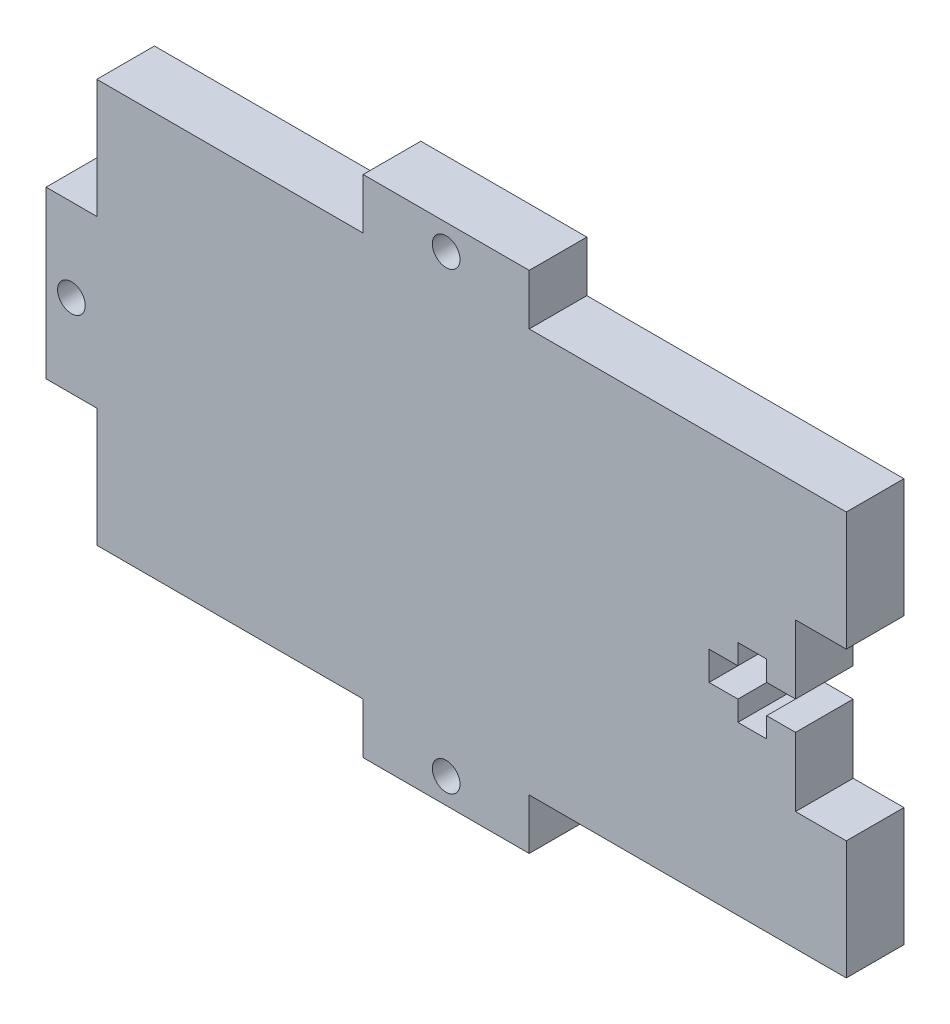
SolidWorks part; units mm, degrees
ref_plane "Front Plane" through (0, 0, 0) normal (0, 0, 1) x (1, 0, 0)
ref_plane "Top Plane" through (0, 0, 0) normal (0, 1, 0) x (1, 0, 0)
ref_plane "Right Plane" through (0, 0, 0) normal (1, 0, 0) x (0, 0, -1)
sketch "Sketch1" plane through (0, 0, 0) normal (0, 0, 1) x (1, 0, 0)
  line L1 (0, 0) -> (82.55, 0)
  line L2 (0, 0) -> (0, 44.45)
  line L3 (0, 44.45) -> (82.55, 44.45)
  line L4 (82.55, 0) -> (82.55, 44.45)
  dimension "D1" = 44.45
  dimension "D2" = 82.55
extrude "Boss-Extrude1" add sketch "Sketch1" along normal blind 6.35
sketch "Sketch2" plane through (0, 0, 6.35) normal (0, 0, 1) x (1, 0, 0)
  line L0 (0, -1.7462) -> (0, 1.7462) construction
  line L1 (0, 31.369) -> (-5.588, 31.369)
  line L2 (0, 31.369) -> (0, 13.081)
  line L3 (0, 13.081) -> (-5.588, 13.081)
  line L4 (-5.588, 31.369) -> (-5.588, 13.081)
  line L6 (0, 44.45) -> (0, 0) construction
  point P6 (-5.588, 22.225)
  point P7 (0, 22.225)
  dimension "D1" = 5.588
  dimension "D2" = 18.288
extrude "Boss-Extrude2" add sketch "Sketch2" against normal blind 6.35
sketch "Sketch5" plane through (0, 0, 6.35) normal (0, 0, 1) x (1, 0, 0)
  line L0 (82.55, 44.45) -> (0, 44.45) construction
  line L1 (29.337, 44.45) -> (47.625, 44.45)
  line L2 (29.337, 44.45) -> (29.337, 50.038)
  line L3 (29.337, 50.038) -> (47.625, 50.038)
  line L4 (47.625, 44.45) -> (47.625, 50.038)
  line L6 (-5.588, 22.225) -> (82.55, 22.225) construction
  line L7 (47.625, 0) -> (47.625, -5.588)
  line L8 (29.337, -5.588) -> (47.625, -5.588)
  line L9 (29.337, 0) -> (29.337, -5.588)
  line L10 (29.337, 0) -> (47.625, 0)
  line L13 (-5.588, 31.369) -> (-5.588, 13.081) construction
  line L14 (82.55, 0) -> (82.55, 44.45) construction
  point P12 (38.481, 0)
  point P18 (38.481, 22.225)
  point P19 (38.481, 44.45)
  dimension "D1" = 18.288
  dimension "D2" = 5.588
extrude "Boss-Extrude3" add sketch "Sketch5" against normal blind 6.35
sketch "Sketch3" plane through (0, 0, 6.35) normal (0, 0, 1) x (1, 0, 0)
  line L0 (82.55, 0) -> (82.55, 44.45) construction
  line L1 (82.55, 13.081) -> (76.962, 13.081)
  line L2 (82.55, 13.081) -> (82.55, 31.369)
  line L3 (82.55, 31.369) -> (76.962, 31.369)
  line L4 (76.962, 13.081) -> (76.962, 31.369)
  line L22 (0, 44.45) -> (0, 31.369)
  line L23 (0, 31.369) -> (-5.588, 31.369)
  line L24 (-5.588, 31.369) -> (-5.588, 13.081)
  line L25 (-5.588, 13.081) -> (0, 13.081)
  line L26 (0, 13.081) -> (0, 0)
  line L27 (0, 0) -> (29.337, 0)
  line L28 (29.337, 0) -> (29.337, -5.588)
  line L29 (29.337, -5.588) -> (47.625, -5.588)
  line L30 (47.625, -5.588) -> (47.625, 0)
  line L31 (47.625, 0) -> (82.55, 0)
  line L32 (82.55, 0) -> (82.55, 44.45)
  line L33 (82.55, 44.45) -> (47.625, 44.45)
  line L34 (47.625, 44.45) -> (47.625, 50.038)
  line L35 (47.625, 50.038) -> (29.337, 50.038)
  line L36 (29.337, 50.038) -> (29.337, 44.45)
  line L37 (29.337, 44.45) -> (0, 44.45)
  line L40 (-5.588, 31.369) -> (-5.588, 13.081) construction
  point P6 (76.962, 22.225)
  point P11 (-5.588, 22.225)
  dimension "D1" = 18.288
  dimension "D2" = 5.588
  dimension "D4" = 0
extrude "Cut-Extrude1" cut sketch "Sketch3" against normal through all
sketch "Sketch6" plane through (0, 0, 6.35) normal (0, 0, 1) x (1, 0, 0)
  line L0 (76.962, 31.369) -> (76.962, 13.081) construction
  line L1 (67.437, 23.8125) -> (70.612, 23.8125)
  line L2 (67.437, 23.8125) -> (67.437, 20.6375)
  line L3 (67.437, 20.6375) -> (70.612, 20.6375)
  line L4 (76.962, 23.8125) -> (76.962, 20.6375)
  line L5 (67.437, 23.8125) -> (76.962, 20.6375) construction
  line L6 (67.437, 20.6375) -> (76.962, 23.8125) construction
  line L7 (70.612, 18.415) -> (73.787, 18.415)
  line L8 (70.612, 18.415) -> (70.612, 20.6375)
  line L9 (70.612, 26.035) -> (73.787, 26.035)
  line L10 (73.787, 18.415) -> (73.787, 20.6375)
  line L11 (70.612, 18.415) -> (73.787, 26.035) construction
  line L12 (70.612, 26.035) -> (73.787, 18.415) construction
  line L13 (70.612, 23.8125) -> (70.612, 26.035)
  line L14 (73.787, 23.8125) -> (76.962, 23.8125)
  line L15 (73.787, 23.8125) -> (73.787, 26.035)
  line L16 (73.787, 20.6375) -> (76.962, 20.6375)
  line L17 (-2.794, 31.369) -> (-2.794, 13.081) construction
  line L18 (0, 31.369) -> (-5.588, 31.369) construction
  line L19 (-5.588, 13.081) -> (0, 13.081) construction
  line L20 (29.337, 50.038) -> (29.337, 44.45) construction
  line L21 (47.625, 44.45) -> (47.625, 50.038) construction
  line L22 (47.625, -5.588) -> (47.625, 0) construction
  line L23 (29.337, 0) -> (29.337, -5.588) construction
  line L24 (29.337, 50.038) -> (29.337, 44.45) construction
  line L25 (47.625, 44.45) -> (47.625, 50.038) construction
  line L26 (47.625, -5.588) -> (47.625, 0) construction
  line L27 (29.337, 0) -> (29.337, -5.588) construction
  line L28 (29.337, 47.244) -> (47.625, 47.244) construction
  line L29 (29.337, -2.794) -> (47.625, -2.794) construction
  circle A0 centre (-2.794, 22.225) radius 1.524
  circle A1 centre (38.481, -2.794) radius 1.524
  circle A2 centre (38.481, 47.244) radius 1.524
  point P0 (72.1995, 22.225)
  point P5 (72.1995, 22.225)
  point P12 (76.962, 22.225)
  dimension "D4" = 3.048
  dimension "D5" = 3.048
  dimension "D6" = 3.048
  dimension "D1" = 3.175
  dimension "D2" = 7.62
  dimension "1/8" = 3.175
  dimension "D3" = 9.525
extrude "Cut-Extrude2" cut sketch "Sketch6" against normal through all
sketch "Sketch7" [suppressed] plane through (0, 0, 0) normal (0, 0, 1) x (1, 0, 0)
  line L0 (15.758, 28.5698) -> (17.4249, 28.5698)
  line L1 (15.758, 29.0778) -> (17.4249, 29.0778)
  line L2 (15.758, 29.0778) -> (15.758, 28.8238)
  line L3 (15.758, 28.8238) -> (17.4249, 28.8238)
  line L4 (17.4249, 29.0778) -> (17.4249, 28.8238)
  line L5 (15.758, 28.5698) -> (15.758, 28.3158)
  line L6 (15.758, 28.3158) -> (17.4249, 28.3158)
  line L7 (17.4249, 28.5698) -> (17.4249, 28.3158)
  line L8 (15.758, 28.0618) -> (17.4249, 28.0618)
  line L9 (15.758, 28.0618) -> (15.758, 27.8078)
  line L10 (15.758, 27.8078) -> (17.4249, 27.8078)
  line L11 (17.4249, 28.0618) -> (17.4249, 27.8078)
  line L12 (15.758, 27.5538) -> (17.4249, 27.5538)
  line L13 (15.758, 27.5538) -> (15.758, 27.2998)
  line L14 (15.758, 27.2998) -> (17.4249, 27.2998)
  line L15 (17.4249, 27.5538) -> (17.4249, 27.2998)
  line L16 (15.758, 27.0458) -> (17.4249, 27.0458)
  line L17 (15.758, 27.0458) -> (15.758, 26.7918)
  line L18 (15.758, 26.7918) -> (17.4249, 26.7918)
  line L19 (17.4249, 27.0458) -> (17.4249, 26.7918)
  line L20 (15.758, 26.5378) -> (17.4249, 26.5378)
  line L21 (15.758, 26.5378) -> (15.758, 26.2838)
  line L22 (15.758, 26.2838) -> (17.4249, 26.2838)
  line L23 (17.4249, 26.5378) -> (17.4249, 26.2838)
  line L24 (15.758, 26.0298) -> (17.4249, 26.0298)
  line L25 (15.758, 26.0298) -> (15.758, 25.7758)
  line L26 (15.758, 25.7758) -> (17.4249, 25.7758)
  line L27 (17.4249, 26.0298) -> (17.4249, 25.7758)
  line L28 (15.758, 25.5218) -> (17.4249, 25.5218)
  line L29 (15.758, 25.5218) -> (15.758, 25.2678)
  line L30 (15.758, 25.2678) -> (17.4249, 25.2678)
  line L31 (17.4249, 25.5218) -> (17.4249, 25.2678)
  line L32 (15.758, 25.0138) -> (17.4249, 25.0138)
  line L33 (15.758, 25.0138) -> (15.758, 24.7598)
  line L34 (15.758, 24.7598) -> (17.4249, 24.7598)
  line L35 (17.4249, 25.0138) -> (17.4249, 24.7598)
  line L36 (15.758, 24.5058) -> (17.4249, 24.5058)
  line L37 (15.758, 24.5058) -> (15.758, 24.2518)
  line L38 (15.758, 24.2518) -> (17.4249, 24.2518)
  line L39 (17.4249, 24.5058) -> (17.4249, 24.2518)
  line L40 (15.758, 23.9978) -> (17.4249, 23.9978)
  line L41 (15.758, 23.9978) -> (15.758, 23.7438)
  line L42 (15.758, 23.7438) -> (17.4249, 23.7438)
  line L43 (17.4249, 23.9978) -> (17.4249, 23.7438)
  line L44 (15.758, 23.4898) -> (17.4249, 23.4898)
  line L45 (15.758, 23.4898) -> (15.758, 23.2358)
  line L46 (15.758, 23.2358) -> (17.4249, 23.2358)
  line L47 (17.4249, 23.4898) -> (17.4249, 23.2358)
  line L48 (15.758, 22.9818) -> (17.4249, 22.9818)
  line L49 (15.758, 22.9818) -> (15.758, 22.7278)
  line L50 (15.758, 22.7278) -> (17.4249, 22.7278)
  line L51 (17.4249, 22.9818) -> (17.4249, 22.7278)
  line L52 (15.758, 22.4738) -> (17.4249, 22.4738)
  line L53 (15.758, 22.4738) -> (15.758, 22.2198)
  line L54 (15.758, 22.2198) -> (17.4249, 22.2198)
  line L55 (17.4249, 22.4738) -> (17.4249, 22.2198)
  line L56 (15.758, 21.9658) -> (17.4249, 21.9658)
  line L57 (15.758, 21.9658) -> (15.758, 21.7118)
  line L58 (15.758, 21.7118) -> (17.4249, 21.7118)
  line L59 (17.4249, 21.9658) -> (17.4249, 21.7118)
  line L60 (15.758, 21.4578) -> (17.4249, 21.4578)
  line L61 (15.758, 21.4578) -> (15.758, 21.2038)
  line L62 (15.758, 21.2038) -> (17.4249, 21.2038)
  line L63 (17.4249, 21.4578) -> (17.4249, 21.2038)
  line L64 (15.758, 20.9498) -> (17.4249, 20.9498)
  line L65 (15.758, 20.9498) -> (15.758, 20.6958)
  line L66 (15.758, 20.6958) -> (17.4249, 20.6958)
  line L67 (17.4249, 20.9498) -> (17.4249, 20.6958)
  line L68 (17.9329, 28.5698) -> (19.5998, 28.5698)
  line L69 (17.9329, 29.0778) -> (19.5998, 29.0778)
  line L70 (17.9329, 29.0778) -> (17.9329, 28.8238)
  line L71 (17.9329, 28.8238) -> (19.5998, 28.8238)
  line L72 (19.5998, 29.0778) -> (19.5998, 28.8238)
  line L73 (17.9329, 28.5698) -> (17.9329, 28.3158)
  line L74 (17.9329, 28.3158) -> (19.5998, 28.3158)
  line L75 (19.5998, 28.5698) -> (19.5998, 28.3158)
  line L76 (17.9329, 28.0618) -> (19.5998, 28.0618)
  line L77 (17.9329, 28.0618) -> (17.9329, 27.8078)
  line L78 (17.9329, 27.8078) -> (19.5998, 27.8078)
  line L79 (19.5998, 28.0618) -> (19.5998, 27.8078)
  line L80 (17.9329, 27.5538) -> (19.5998, 27.5538)
  line L81 (17.9329, 27.5538) -> (17.9329, 27.2998)
  line L82 (17.9329, 27.2998) -> (19.5998, 27.2998)
  line L83 (19.5998, 27.5538) -> (19.5998, 27.2998)
  line L84 (17.9329, 27.0458) -> (19.5998, 27.0458)
  line L85 (17.9329, 27.0458) -> (17.9329, 26.7918)
  line L86 (17.9329, 26.7918) -> (19.5998, 26.7918)
  line L87 (19.5998, 27.0458) -> (19.5998, 26.7918)
  line L88 (17.9329, 26.5378) -> (19.5998, 26.5378)
  line L89 (17.9329, 26.5378) -> (17.9329, 26.2838)
  line L90 (17.9329, 26.2838) -> (19.5998, 26.2838)
  line L91 (19.5998, 26.5378) -> (19.5998, 26.2838)
  line L92 (17.9329, 26.0298) -> (19.5998, 26.0298)
  line L93 (17.9329, 26.0298) -> (17.9329, 25.7758)
  line L94 (17.9329, 25.7758) -> (19.5998, 25.7758)
  line L95 (19.5998, 26.0298) -> (19.5998, 25.7758)
  line L96 (17.9329, 25.5218) -> (19.5998, 25.5218)
  line L97 (17.9329, 25.5218) -> (17.9329, 25.2678)
  line L98 (17.9329, 25.2678) -> (19.5998, 25.2678)
  line L99 (19.5998, 25.5218) -> (19.5998, 25.2678)
  line L100 (17.9329, 25.0138) -> (19.5998, 25.0138)
  line L101 (17.9329, 25.0138) -> (17.9329, 24.7598)
  line L102 (17.9329, 24.7598) -> (19.5998, 24.7598)
  line L103 (19.5998, 25.0138) -> (19.5998, 24.7598)
  line L104 (17.9329, 24.5058) -> (19.5998, 24.5058)
  line L105 (17.9329, 24.5058) -> (17.9329, 24.2518)
  line L106 (17.9329, 24.2518) -> (19.5998, 24.2518)
  line L107 (19.5998, 24.5058) -> (19.5998, 24.2518)
  line L108 (17.9329, 23.9978) -> (19.5998, 23.9978)
  line L109 (17.9329, 23.9978) -> (17.9329, 23.7438)
  line L110 (17.9329, 23.7438) -> (19.5998, 23.7438)
  line L111 (19.5998, 23.9978) -> (19.5998, 23.7438)
  line L112 (17.9329, 23.4898) -> (19.5998, 23.4898)
  line L113 (17.9329, 23.4898) -> (17.9329, 23.2358)
  line L114 (17.9329, 23.2358) -> (19.5998, 23.2358)
  line L115 (19.5998, 23.4898) -> (19.5998, 23.2358)
  line L116 (20.1078, 29.0778) -> (21.7746, 29.0778)
  line L117 (20.1078, 29.0778) -> (20.1078, 28.8238)
  line L118 (20.1078, 28.8238) -> (21.7746, 28.8238)
  line L119 (21.7746, 29.0778) -> (21.7746, 28.8238)
  line L120 (20.1078, 28.5698) -> (20.1078, 28.3158)
  line L121 (20.1078, 28.3158) -> (21.7746, 28.3158)
  line L122 (21.7746, 28.5698) -> (21.7746, 28.3158)
  line L123 (20.1078, 28.5698) -> (21.7746, 28.5698)
  line L124 (20.1078, 28.0618) -> (20.1078, 27.8078)
  line L125 (20.1078, 27.8078) -> (21.7746, 27.8078)
  line L126 (21.7746, 28.0618) -> (21.7746, 27.8078)
  line L127 (20.1078, 28.0618) -> (21.7746, 28.0618)
  line L128 (20.1078, 27.5538) -> (20.1078, 27.2998)
  line L129 (20.1078, 27.2998) -> (21.7746, 27.2998)
  line L130 (21.7746, 27.5538) -> (21.7746, 27.2998)
  line L131 (20.1078, 27.5538) -> (21.7746, 27.5538)
  line L132 (20.1078, 27.0458) -> (20.1078, 26.7918)
  line L133 (20.1078, 26.7918) -> (21.7746, 26.7918)
  line L134 (21.7746, 27.0458) -> (21.7746, 26.7918)
  line L135 (20.1078, 27.0458) -> (21.7746, 27.0458)
  line L136 (15.758, 29.0778) -> (31.3136, 29.0778) construction
  line L137 (20.1078, 26.5378) -> (20.1078, 26.2838)
  line L138 (20.1078, 26.2838) -> (21.7746, 26.2838)
  line L139 (21.7746, 26.5378) -> (21.7746, 26.2838)
  line L140 (20.1078, 26.5378) -> (21.7746, 26.5378)
  line L141 (20.1078, 26.0298) -> (20.1078, 25.7758)
  line L142 (20.1078, 25.7758) -> (21.7746, 25.7758)
  line L143 (21.7746, 26.0298) -> (21.7746, 25.7758)
  line L144 (20.1078, 26.0298) -> (21.7746, 26.0298)
  line L145 (20.1078, 25.5218) -> (20.1078, 25.2678)
  line L146 (20.1078, 25.2678) -> (21.7746, 25.2678)
  line L147 (21.7746, 25.5218) -> (21.7746, 25.2678)
  line L148 (20.1078, 25.5218) -> (21.7746, 25.5218)
  line L149 (20.1078, 25.0138) -> (20.1078, 24.7598)
  line L150 (20.1078, 24.7598) -> (21.7746, 24.7598)
  line L151 (21.7746, 25.0138) -> (21.7746, 24.7598)
  line L152 (20.1078, 25.0138) -> (21.7746, 25.0138)
  line L153 (20.1078, 24.5058) -> (20.1078, 24.2518)
  line L154 (20.1078, 24.2518) -> (21.7746, 24.2518)
  line L155 (21.7746, 24.5058) -> (21.7746, 24.2518)
  line L156 (20.1078, 24.5058) -> (21.7746, 24.5058)
  line L157 (20.1078, 23.9978) -> (20.1078, 23.7438)
  line L158 (20.1078, 23.7438) -> (21.7746, 23.7438)
  line L159 (21.7746, 23.9978) -> (21.7746, 23.7438)
  line L160 (20.1078, 23.9978) -> (21.7746, 23.9978)
  line L161 (20.1078, 23.4898) -> (20.1078, 23.2358)
  line L162 (20.1078, 23.2358) -> (21.7746, 23.2358)
  line L163 (21.7746, 23.4898) -> (21.7746, 23.2358)
  line L164 (20.1078, 23.4898) -> (21.7746, 23.4898)
  line L165 (20.1078, 22.9818) -> (20.1078, 22.7278)
  line L166 (20.1078, 22.7278) -> (21.7746, 22.7278)
  line L167 (21.7746, 22.9818) -> (21.7746, 22.7278)
  line L168 (20.1078, 22.9818) -> (21.7746, 22.9818)
  line L169 (20.1078, 22.4738) -> (20.1078, 22.2198)
  line L170 (20.1078, 22.2198) -> (21.7746, 22.2198)
  line L171 (21.7746, 22.4738) -> (21.7746, 22.2198)
  line L172 (20.1078, 22.4738) -> (21.7746, 22.4738)
  line L173 (20.1078, 21.9658) -> (20.1078, 21.7118)
  line L174 (20.1078, 21.7118) -> (21.7746, 21.7118)
  line L175 (21.7746, 21.9658) -> (21.7746, 21.7118)
  line L176 (20.1078, 21.9658) -> (21.7746, 21.9658)
  line L177 (20.1078, 21.4578) -> (20.1078, 21.2038)
  line L178 (20.1078, 21.2038) -> (21.7746, 21.2038)
  line L179 (21.7746, 21.4578) -> (21.7746, 21.2038)
  line L180 (20.1078, 21.4578) -> (21.7746, 21.4578)
  line L181 (20.1078, 20.9498) -> (20.1078, 20.6958)
  line L182 (20.1078, 20.6958) -> (21.7746, 20.6958)
  line L183 (21.7746, 20.9498) -> (21.7746, 20.6958)
  line L184 (20.1078, 20.9498) -> (21.7746, 20.9498)
  line L185 (22.2826, 29.0778) -> (23.9495, 29.0778)
  line L186 (22.2826, 29.0778) -> (22.2826, 28.8238)
  line L187 (22.2826, 28.8238) -> (23.9495, 28.8238)
  line L188 (23.9495, 29.0778) -> (23.9495, 28.8238)
  line L189 (22.2826, 28.5698) -> (22.2826, 28.3158)
  line L190 (22.2826, 28.3158) -> (23.9495, 28.3158)
  line L191 (23.9495, 28.5698) -> (23.9495, 28.3158)
  line L192 (22.2826, 28.5698) -> (23.9495, 28.5698)
  line L193 (22.2826, 28.0618) -> (22.2826, 27.8078)
  line L194 (22.2826, 27.8078) -> (23.9495, 27.8078)
  line L195 (23.9495, 28.0618) -> (23.9495, 27.8078)
  line L196 (22.2826, 28.0618) -> (23.9495, 28.0618)
  line L197 (22.2826, 27.5538) -> (22.2826, 27.2998)
  line L198 (22.2826, 27.2998) -> (23.9495, 27.2998)
  line L199 (23.9495, 27.5538) -> (23.9495, 27.2998)
  line L200 (22.2826, 27.5538) -> (23.9495, 27.5538)
  line L201 (24.759, 28.5698) -> (24.759, 28.3158)
  line L202 (24.759, 28.3158) -> (27.7294, 29.8293)
  line L203 (24.759, 28.5698) -> (27.7294, 30.0833)
  line L204 (27.7294, 30.0833) -> (27.7294, 29.8293)
  line L205 (22.2826, 26.5378) -> (22.2826, 26.2838)
  line L206 (22.2826, 26.2838) -> (23.9495, 26.2838)
  line L207 (23.9495, 26.5378) -> (23.9495, 26.2838)
  line L208 (22.2826, 26.5378) -> (23.9495, 26.5378)
  line L209 (22.2826, 26.0298) -> (22.2826, 25.7758)
  line L210 (22.2826, 25.7758) -> (23.9495, 25.7758)
  line L211 (23.9495, 26.0298) -> (23.9495, 25.7758)
  line L212 (22.2826, 26.0298) -> (23.9495, 26.0298)
  line L213 (22.2826, 25.5218) -> (22.2826, 25.2678)
  line L214 (22.2826, 25.2678) -> (23.9495, 25.2678)
  line L215 (23.9495, 25.5218) -> (23.9495, 25.2678)
  line L216 (22.2826, 25.5218) -> (23.9495, 25.5218)
  line L217 (22.2826, 25.0138) -> (22.2826, 24.7598)
  line L218 (22.2826, 24.7598) -> (23.9495, 24.7598)
  line L219 (23.9495, 25.0138) -> (23.9495, 24.7598)
  line L220 (22.2826, 25.0138) -> (23.9495, 25.0138)
  line L221 (22.2826, 24.5058) -> (22.2826, 24.2518)
  line L222 (22.2826, 24.2518) -> (23.9495, 24.2518)
  line L223 (23.9495, 24.5058) -> (23.9495, 24.2518)
  line L224 (22.2826, 24.5058) -> (23.9495, 24.5058)
  line L225 (22.2826, 23.9978) -> (22.2826, 23.7438)
  line L226 (22.2826, 23.7438) -> (23.9495, 23.7438)
  line L227 (23.9495, 23.9978) -> (23.9495, 23.7438)
  line L228 (22.2826, 23.9978) -> (23.9495, 23.9978)
  line L229 (22.2826, 23.4898) -> (22.2826, 23.2358)
  line L230 (22.2826, 23.2358) -> (23.9495, 23.2358)
  line L231 (23.9495, 23.4898) -> (23.9495, 23.2358)
  line L232 (22.2826, 23.4898) -> (23.9495, 23.4898)
  line L233 (22.2826, 22.9818) -> (22.2826, 22.7278)
  line L234 (22.2826, 22.7278) -> (23.9495, 22.7278)
  line L235 (23.9495, 22.9818) -> (23.9495, 22.7278)
  line L236 (22.2826, 22.9818) -> (23.9495, 22.9818)
  line L237 (22.2826, 22.4738) -> (22.2826, 22.2198)
  line L238 (22.2826, 22.2198) -> (23.9495, 22.2198)
  line L239 (23.9495, 22.4738) -> (23.9495, 22.2198)
  line L240 (22.2826, 22.4738) -> (23.9495, 22.4738)
  line L241 (22.2826, 21.9658) -> (22.2826, 21.7118)
  line L242 (22.2826, 21.7118) -> (23.9495, 21.7118)
  line L243 (23.9495, 21.9658) -> (23.9495, 21.7118)
  line L244 (22.2826, 21.9658) -> (23.9495, 21.9658)
  line L245 (22.2826, 21.4578) -> (22.2826, 21.2038)
  line L246 (22.2826, 21.2038) -> (23.9495, 21.2038)
  line L247 (23.9495, 21.4578) -> (23.9495, 21.2038)
  line L248 (22.2826, 21.4578) -> (23.9495, 21.4578)
  line L249 (22.2826, 20.9498) -> (22.2826, 20.6958)
  line L250 (22.2826, 20.6958) -> (23.9495, 20.6958)
  line L251 (23.9495, 20.9498) -> (23.9495, 20.6958)
  line L252 (22.2826, 20.9498) -> (23.9495, 20.9498)
  line L253 (24.759, 29.0778) -> (24.759, 28.8238)
  line L254 (24.759, 28.8238) -> (27.7294, 30.3373)
  line L255 (27.7294, 30.5913) -> (27.7294, 30.3373)
  line L256 (24.759, 29.0778) -> (27.7294, 30.5913)
  line L257 (22.2826, 27.0458) -> (22.2826, 26.7918)
  line L258 (22.2826, 26.7918) -> (23.9495, 26.7918)
  line L259 (23.9495, 27.0458) -> (23.9495, 26.7918)
  line L260 (22.2826, 27.0458) -> (23.9495, 27.0458)
  line L261 (24.759, 28.0618) -> (24.759, 27.8078)
  line L262 (24.759, 27.8078) -> (27.7294, 29.3213)
  line L263 (24.759, 28.0618) -> (27.7294, 29.5753)
  line L264 (27.7294, 29.5753) -> (27.7294, 29.3213)
  line L265 (24.759, 27.5538) -> (24.759, 27.2998)
  line L266 (24.759, 27.2998) -> (27.7294, 28.8133)
  line L267 (24.759, 27.5538) -> (27.7294, 29.0673)
  line L268 (27.7294, 29.0673) -> (27.7294, 28.8133)
  line L269 (24.759, 26.5378) -> (24.759, 26.2838)
  line L270 (24.759, 26.2838) -> (26.2442, 27.0406)
  line L271 (26.2442, 27.2946) -> (26.2442, 27.0406)
  line L272 (24.759, 26.5378) -> (26.2442, 27.2946)
  line L273 (24.759, 25.7758) -> (26.2442, 26.5326)
  line L274 (26.2442, 26.7866) -> (26.2442, 26.5326)
  line L275 (24.759, 26.0298) -> (24.759, 25.7758)
  line L276 (24.759, 26.0298) -> (26.2442, 26.7866)
  line L277 (24.759, 25.2678) -> (26.2442, 26.0246)
  line L278 (26.2442, 26.2786) -> (26.2442, 26.0246)
  line L279 (24.759, 25.5218) -> (24.759, 25.2678)
  line L280 (24.759, 25.5218) -> (26.2442, 26.2786)
  line L281 (24.759, 24.7598) -> (26.2442, 25.5166)
  line L282 (26.2442, 25.7706) -> (26.2442, 25.5166)
  line L283 (24.759, 25.0138) -> (24.759, 24.7598)
  line L284 (24.759, 25.0138) -> (26.2442, 25.7706)
  line L285 (24.759, 24.2518) -> (26.2442, 25.0086)
  line L286 (26.2442, 25.2626) -> (26.2442, 25.0086)
  line L287 (24.759, 24.5058) -> (24.759, 24.2518)
  line L288 (24.759, 24.5058) -> (26.2442, 25.2626)
  line L289 (24.759, 23.7438) -> (26.2442, 24.5006)
  line L290 (26.2442, 24.7546) -> (26.2442, 24.5006)
  line L291 (24.759, 23.9978) -> (24.759, 23.7438)
  line L292 (24.759, 23.9978) -> (26.2442, 24.7546)
  line L293 (24.759, 23.2358) -> (26.2442, 23.9926)
  line L294 (26.2442, 24.2466) -> (26.2442, 23.9926)
  line L295 (24.759, 23.4898) -> (24.759, 23.2358)
  line L296 (24.759, 23.4898) -> (26.2442, 24.2466)
  line L297 (24.759, 22.7278) -> (26.2442, 23.4846)
  line L298 (26.2442, 23.7386) -> (26.2442, 23.4846)
  line L299 (24.759, 22.9818) -> (24.759, 22.7278)
  line L300 (24.759, 22.9818) -> (26.2442, 23.7386)
  line L301 (24.759, 22.2198) -> (26.2442, 22.9766)
  line L302 (26.2442, 23.2306) -> (26.2442, 22.9766)
  line L303 (24.759, 22.4738) -> (24.759, 22.2198)
  line L304 (24.759, 22.4738) -> (26.2442, 23.2306)
  line L305 (24.759, 21.7118) -> (26.2442, 22.4686)
  line L306 (26.2442, 22.7226) -> (26.2442, 22.4686)
  line L307 (24.759, 21.9658) -> (24.759, 21.7118)
  line L308 (24.759, 21.9658) -> (26.2442, 22.7226)
  line L309 (24.759, 21.2038) -> (26.2442, 21.9606)
  line L310 (26.2442, 22.2146) -> (26.2442, 21.9606)
  line L311 (24.759, 21.4578) -> (24.759, 21.2038)
  line L312 (24.759, 21.4578) -> (26.2442, 22.2146)
  line L313 (24.759, 20.6958) -> (26.2442, 21.4526)
  line L314 (26.2442, 21.7066) -> (26.2442, 21.4526)
  line L315 (24.759, 20.9498) -> (24.759, 20.6958)
  line L316 (24.759, 20.9498) -> (26.2442, 21.7066)
  dimension "D1" = 1.6669
  dimension "D2" = 0.254
  dimension "D3" = 17
  dimension "D4" = 1.6669
  dimension "D5" = 0.508
  dimension "D6" = 1.6669
  dimension "D7" = 0.254
  dimension "D9" = 0.254
  dimension "D10" = 0.508
  dimension "D12" = 1.6669
  dimension "D13" = 0.254
  dimension "D14" = 0.508
  dimension "D16" = 3.3337
  dimension "D17" = 0.254
  dimension "D18" = 27
  dimension "D19" = 0.8095
  dimension "D21" = 1.016
  dimension "D22" = 0.254
  dimension "D23" = 1.6669
  dimension "D8" = 12
  dimension "D11" = 17
  dimension "D15" = 17
  dimension "D20" = 4
  dimension "D24" = 12
